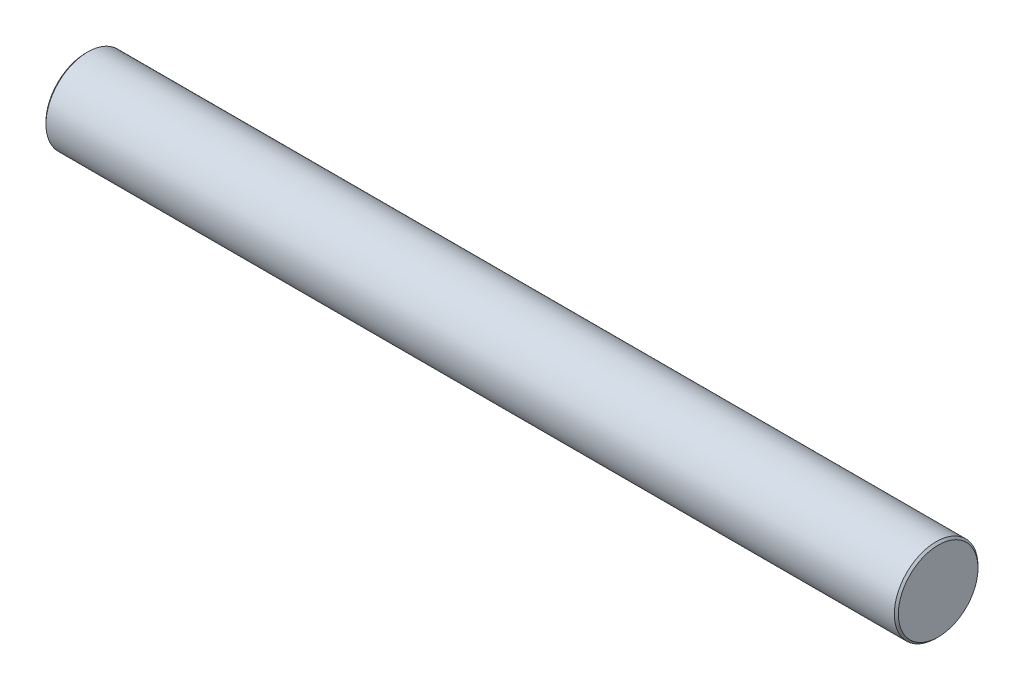
SolidWorks part; units mm, degrees
ref_plane "Front Plane" through (0, 0, 0) normal (0, 0, 1) x (1, 0, 0)
ref_plane "Top Plane" through (0, 0, 0) normal (0, 1, 0) x (1, 0, 0)
ref_plane "Right Plane" through (0, 0, 0) normal (1, 0, 0) x (0, 0, -1)
sketch "Sketch1" plane through (0, 0, 0) normal (1, 0, 0) x (0, 0, -1)
  circle A0 centre (0, 0) radius 15.9
  dimension "D1" = 31.8
extrude "Boss-Extrude1" add sketch "Sketch1" along normal mid plane 323.85
chamfer "Chamfer1" distance 0.762 angle 45 2 edges at (161.925, 0, -15.9) (-161.925, 0, -15.9)
